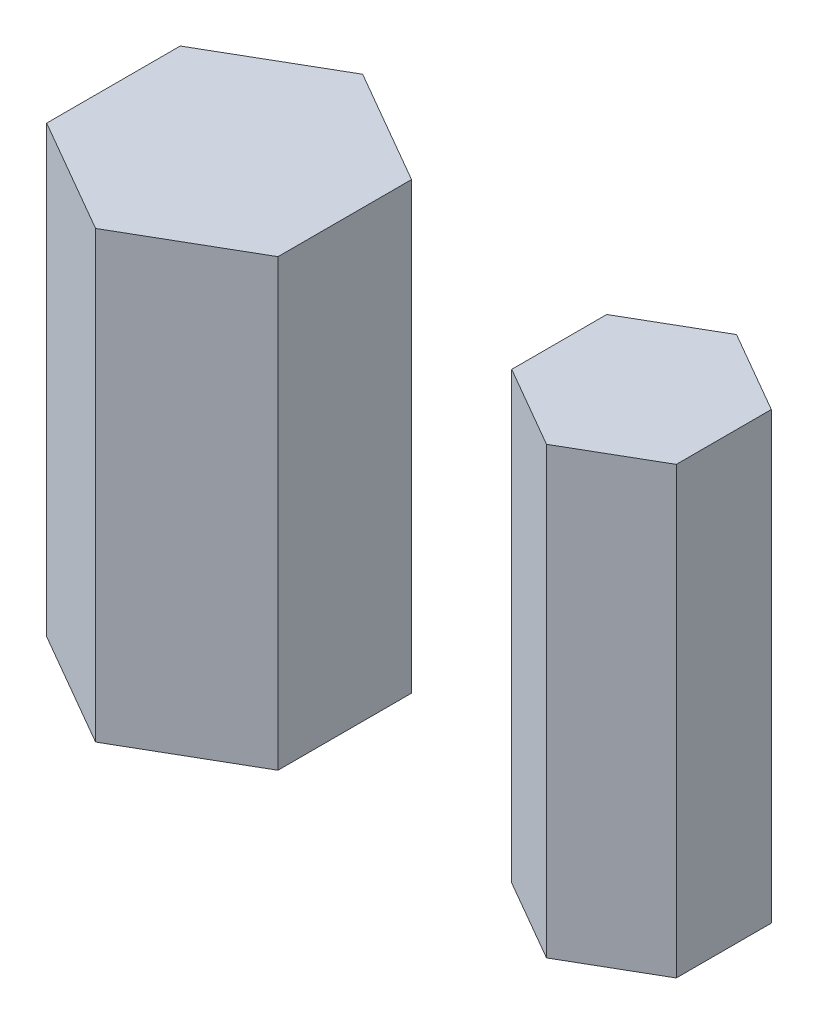
SolidWorks part; units mm, degrees
ref_plane "Front Plane" through (0, 0, 0) normal (0, 0, 1) x (1, 0, 0)
ref_plane "Top Plane" through (0, 0, 0) normal (0, 1, 0) x (1, 0, 0)
ref_plane "Right Plane" through (0, 0, 0) normal (1, 0, 0) x (0, 0, -1)
sketch "Sketch1" plane through (0, 0, 0) normal (0, 1, 0) x (1, 0, 0)
  line L1 (0, -3.0022) -> (2.6, -1.5011)
  line L2 (2.6, -1.5011) -> (2.6, 1.5011)
  line L3 (2.6, 1.5011) -> (0, 3.0022)
  line L4 (0, 3.0022) -> (-2.6, 1.5011)
  line L5 (-2.6, 1.5011) -> (-2.6, -1.5011)
  line L6 (-2.6, -1.5011) -> (0, -3.0022)
  line L7 (9.2713, -2.1362) -> (11.1213, -1.0681)
  line L8 (11.1213, -1.0681) -> (11.1213, 1.0681)
  line L9 (11.1213, 1.0681) -> (9.2713, 2.1362)
  line L10 (9.2713, 2.1362) -> (7.4213, 1.0681)
  line L11 (7.4213, 1.0681) -> (7.4213, -1.0681)
  line L12 (7.4213, -1.0681) -> (9.2713, -2.1362)
  circle A0 centre (0, 0) radius 2.6 construction
  circle A1 centre (9.2713, 0) radius 1.85 construction
  dimension "D1" = 5.2
  dimension "D2" = 3.7
extrude "Boss-Extrude1" add sketch "Sketch1" along normal blind 10
